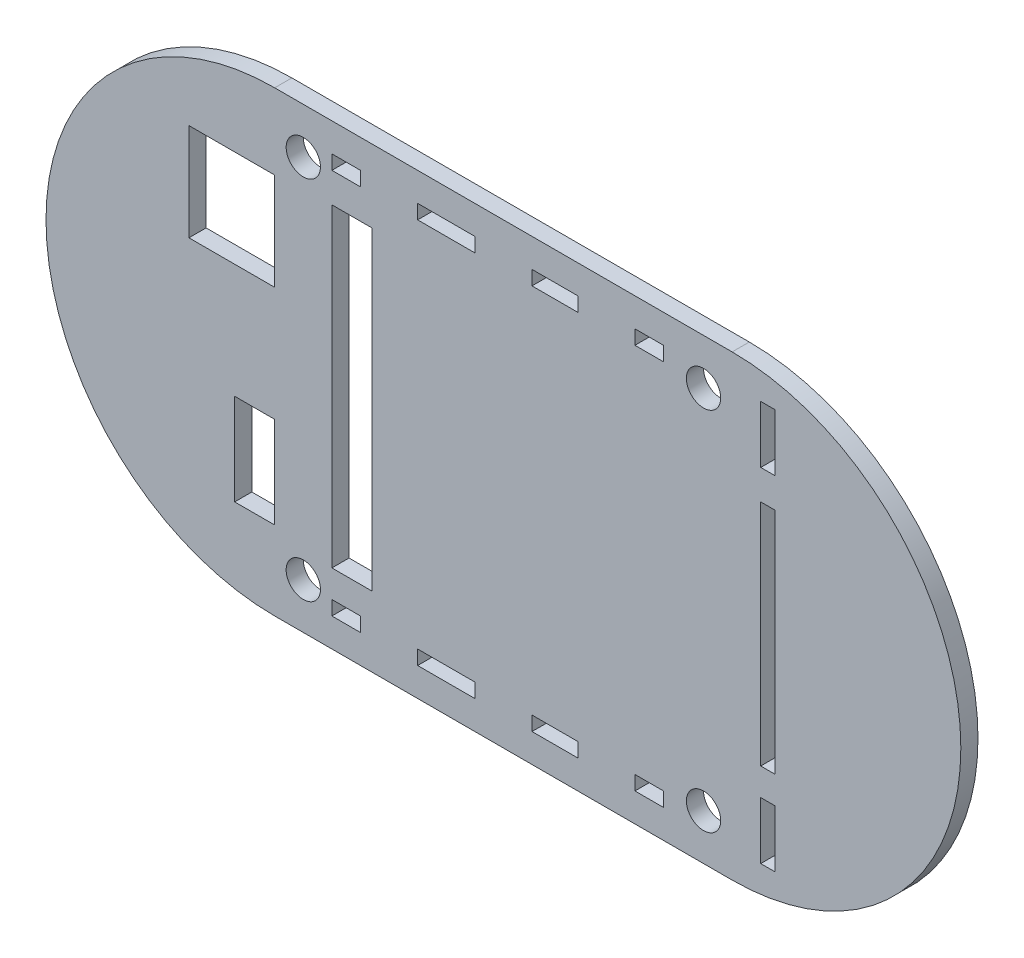
SolidWorks part; units mm, degrees
ref_plane "Front Plane" through (0, 0, 0) normal (0, 0, 1) x (1, 0, 0)
ref_plane "Top Plane" through (0, 0, 0) normal (0, 1, 0) x (1, 0, 0)
ref_plane "Right Plane" through (0, 0, 0) normal (1, 0, 0) x (0, 0, -1)
sketch "Sketch1" plane through (0, 0, 0) normal (0, 0, 1) x (1, 0, 0)
  line L0 (133.9528, 0.2192) -> (-107.5854, 0.2192) construction
  line L1 (40, 40.2192) -> (-40, 40.2192)
  line L2 (40, 87.2108) -> (40, -83.2418) construction
  line L3 (40, -39.7808) -> (-40, -39.7808)
  line L4 (-40, 79.3124) -> (-40, -89.3567) construction
  arc A0 (40, -39.7808) -> (40, 40.2192) centre (40, 0.2192) ccw
  arc A1 (-40, 40.2192) -> (-40, -39.7808) centre (-40, 0.2192) ccw
  point P0 (0, 0)
  dimension "D1" = 80
  dimension "D2" = 80
extrude "Boss-Extrude1" add sketch "Sketch1" along normal blind 3
sketch "Sketch2" plane through (0, 0, 0) normal (0, 0, -1) x (-1, 0, 0)
  line L0 (0, 0) -> (-105.1665, 0) construction
  line L1 (23, 27.5) -> (30, 27.5)
  line L2 (23, 27.5) -> (23, -27.5)
  line L3 (23, -27.5) -> (30, -27.5)
  line L4 (30, 27.5) -> (30, -27.5)
  line L5 (0, 0) -> (106.41, 0) construction
  line L6 (40, 0) -> (40, 146.3781) construction
  line L7 (-47.5, 20) -> (-45, 20)
  line L8 (-47.5, 20) -> (-47.5, -20)
  line L9 (-47.5, -20) -> (-45, -20)
  line L10 (-45, 20) -> (-45, -20)
  line L11 (-47.5, 35.2192) -> (-45, 35.2192)
  line L12 (-47.5, 35.2192) -> (-47.5, 25.2192)
  line L13 (-47.5, 25.2192) -> (-45, 25.2192)
  line L14 (-45, 35.2192) -> (-45, 25.2192)
  line L15 (-45, -34.7808) -> (-47.5, -34.7808)
  line L16 (-45, -34.7808) -> (-45, -24.7808)
  line L17 (-45, -24.7808) -> (-47.5, -24.7808)
  line L18 (-47.5, -34.7808) -> (-47.5, -24.7808)
  line L19 (25, 35.2192) -> (30, 35.2192)
  line L20 (25, 35.2192) -> (25, 32.7192)
  line L21 (25, 32.7192) -> (30, 32.7192)
  line L22 (30, 35.2192) -> (30, 32.7192)
  line L23 (30, -34.7808) -> (25, -34.7808)
  line L24 (30, -34.7808) -> (30, -32.2808)
  line L25 (30, -32.2808) -> (25, -32.2808)
  line L26 (25, -34.7808) -> (25, -32.2808)
  line L27 (-28, 35.2192) -> (-23, 35.2192)
  line L28 (-28, 35.2192) -> (-28, 32.7192)
  line L29 (-28, 32.7192) -> (-23, 32.7192)
  line L30 (-23, 35.2192) -> (-23, 32.7192)
  line L31 (-13, 35.2192) -> (-5, 35.2192)
  line L32 (-13, 35.2192) -> (-13, 32.7192)
  line L33 (-13, 32.7192) -> (-5, 32.7192)
  line L34 (-5, 35.2192) -> (-5, 32.7192)
  line L35 (5, 35.2192) -> (15, 35.2192)
  line L36 (5, 35.2192) -> (5, 32.7192)
  line L37 (5, 32.7192) -> (15, 32.7192)
  line L38 (15, 35.2192) -> (15, 32.7192)
  line L39 (-28, -34.7808) -> (-23, -34.7808)
  line L40 (-28, -34.7808) -> (-28, -32.2808)
  line L41 (-28, -32.2808) -> (-23, -32.2808)
  line L42 (-23, -34.7808) -> (-23, -32.2808)
  line L43 (-13, -32.2808) -> (-5, -32.2808)
  line L44 (-13, -32.2808) -> (-13, -34.7808)
  line L45 (-13, -34.7808) -> (-5, -34.7808)
  line L46 (-5, -32.2808) -> (-5, -34.7808)
  line L47 (5, -32.2808) -> (15, -32.2808)
  line L48 (5, -32.2808) -> (5, -34.7808)
  line L49 (5, -34.7808) -> (15, -34.7808)
  line L50 (15, -32.2808) -> (15, -34.7808)
  line L51 (40, -10) -> (47, -10)
  line L52 (40, -10) -> (40, -26)
  line L53 (40, -26) -> (47, -26)
  line L54 (47, -10) -> (47, -26)
  line L55 (40, 27) -> (55, 27)
  line L56 (40, 27) -> (40, 10)
  line L57 (40, 10) -> (55, 10)
  line L58 (55, 27) -> (55, 10)
  line L59 (40, -39.7808) -> (-40, -39.7808) construction
  line L60 (-40, 40.2192) -> (40, 40.2192) construction
  line L61 (-40, 40.2192) -> (-40, 134.9711) construction
  line L62 (40, 0) -> (40, -142.3648) construction
  line L63 (-40, 134.9711) -> (-40, -132.4177) construction
  line L64 (84.1119, 27.2192) -> (-107.3246, 27.2192) construction
  line L65 (90.2578, -26.7808) -> (-102.5892, -26.7808) construction
  line L66 (-40, 40.2192) -> (40, 40.2192) construction
  circle A0 centre (-35, 32.2192) radius 3
  circle A1 centre (-35, -31.7808) radius 3
  circle A2 centre (35, 32.2192) radius 3
  circle A3 centre (35, -31.7808) radius 3
  point P7 (26.5, 27.5)
  point P9 (26.5, -27.5)
  point P54 (-25.5, 35.2192)
  point P80 (-11.6064, 27.2192)
  dimension "D52" = 6
  dimension "D53" = 5
  dimension "D60" = 6
  dimension "D61" = 6
  dimension "D62" = 6
  dimension "D1" = 27.5
  dimension "D2" = 55
  dimension "D3" = 7
  dimension "D4" = 40
  dimension "D5" = 20
  dimension "D6" = 2.5
  dimension "D7" = 10
  dimension "D8" = 2.5
  dimension "D9" = 10
  dimension "D10" = 2.5
  dimension "D11" = 5
  dimension "D12" = 5
  dimension "D13" = 2.5
  dimension "D14" = 2.5
  dimension "D15" = 5
  dimension "D16" = 5
  dimension "D17" = 2.5
  dimension "D18" = 8
  dimension "D19" = 8
  dimension "D20" = 2.5
  dimension "D21" = 2.5
  dimension "D22" = 10
  dimension "D23" = 10
  dimension "D24" = 2.5
  dimension "D25" = 2.5
  dimension "D26" = 16
  dimension "D27" = 7
  dimension "D28" = 17
  dimension "D29" = 15
  dimension "D30" = 2.5
  dimension "D31" = 5
  dimension "D32" = 5
  dimension "D33" = 5
  dimension "D34" = 5
  dimension "D35" = 5
  dimension "D36" = 5
  dimension "D37" = 5
  dimension "D38" = 5
  dimension "D39" = 5
  dimension "D40" = 23
  dimension "D41" = 45
  dimension "D42" = 30
  dimension "D43" = 30
  dimension "D44" = 10
  dimension "D45" = 10
  dimension "D46" = 10
  dimension "D47" = 10
  dimension "D48" = 10
  dimension "D49" = 10
  dimension "D50" = 13
  dimension "D51" = 13
  dimension "D54" = 5
  dimension "D55" = 5
  dimension "D56" = 5
  dimension "D57" = 5
  dimension "D58" = 5
  dimension "D59" = 5
  dimension "D63" = 5
  dimension "D64" = 5
  dimension "D65" = 5
  dimension "D66" = 5
  dimension "D67" = 10
  dimension "D68" = 10
  dimension "D69" = 10
  dimension "D70" = 10
extrude "Cut-Extrude1" cut sketch "Sketch2" against normal up to surface (3 mm away)
